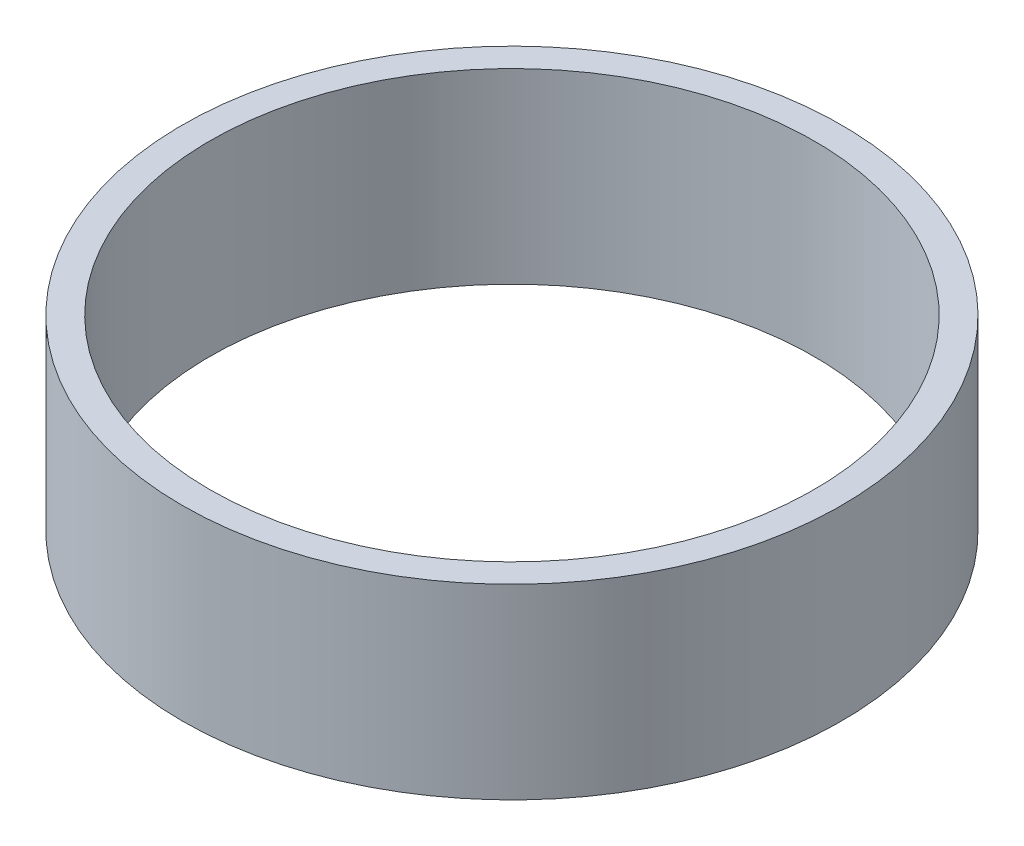
SolidWorks part; units mm, degrees
ref_plane "Front Plane" through (0, 0, 0) normal (0, 0, 1) x (1, 0, 0)
ref_plane "Top Plane" through (0, 0, 0) normal (0, 1, 0) x (1, 0, 0)
ref_plane "Right Plane" through (0, 0, 0) normal (1, 0, 0) x (0, 0, -1)
sketch "Sketch1" plane through (0, 0, 0) normal (0, 1, 0) x (1, 0, 0)
  circle A0 centre (0, 0) radius 60
  circle A1 centre (0, 0) radius 55
  dimension "D1" = 120
  dimension "D2" = 5
extrude "Boss-Extrude1" add sketch "Sketch1" along normal mid plane 34
